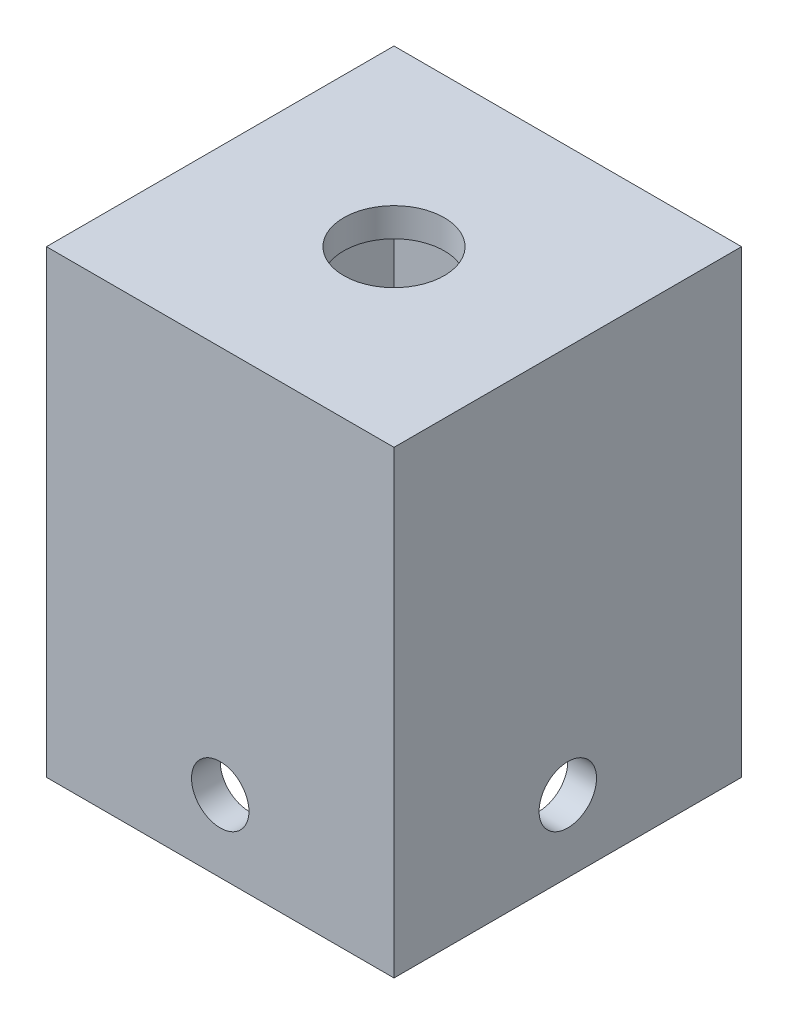
SolidWorks part; units mm, degrees
ref_plane "Front Plane" through (0, 0, 0) normal (0, 0, 1) x (1, 0, 0)
ref_plane "Top Plane" through (0, 0, 0) normal (0, 1, 0) x (1, 0, 0)
ref_plane "Right Plane" through (0, 0, 0) normal (1, 0, 0) x (0, 0, -1)
sketch "Sketch1" plane through (0, 0, 0) normal (0, 1, 0) x (1, 0, 0)
  line L1 (10.1, 10.1) -> (-10.1, 10.1)
  line L2 (10.1, 10.1) -> (10.1, -10.1)
  line L3 (10.1, -10.1) -> (-10.1, -10.1)
  line L4 (-10.1, 10.1) -> (-10.1, -10.1)
  line L5 (10.1, 10.1) -> (-10.1, -10.1) construction
  line L6 (10.1, -10.1) -> (-10.1, 10.1) construction
  line L7 (12.1, 12.1) -> (-12.1, 12.1)
  line L8 (12.1, 12.1) -> (12.1, -12.1)
  line L9 (12.1, -12.1) -> (-12.1, -12.1)
  line L10 (-12.1, 12.1) -> (-12.1, -12.1)
  line L11 (12.1, 12.1) -> (-12.1, -12.1) construction
  line L12 (12.1, -12.1) -> (-12.1, 12.1) construction
  point P0 (0, 0)
  point P6 (0, 0)
  dimension "D1" = 20.2
  dimension "D2" = 20.2
  dimension "D3" = 2
  dimension "D4" = 2
extrude "Boss-Extrude1" add sketch "Sketch1" along normal blind 30
sketch "Sketch2" plane through (0, 0, 12.1) normal (0, 0, 1) x (1, 0, 0)
  circle A0 centre (0, 5) radius 2
  dimension "D1" = 4
  dimension "D2" = 5
extrude "Cut-Extrude1" cut sketch "Sketch2" against normal blind 30
sketch "Sketch3" plane through (12.1, 0, 0) normal (1, 0, 0) x (0, 0, -1)
  circle A0 centre (0, 5) radius 2
  dimension "D1" = 4
  dimension "D2" = 5
extrude "Cut-Extrude2" cut sketch "Sketch3" against normal blind 30
sketch "Sketch4" plane through (0, 30, 0) normal (0, 1, 0) x (1, 0, 0)
  line L1 (12.1, 12.1) -> (-12.1, 12.1)
  line L2 (12.1, 12.1) -> (12.1, -12.1)
  line L3 (12.1, -12.1) -> (-12.1, -12.1)
  line L4 (-12.1, 12.1) -> (-12.1, -12.1)
  line L5 (12.1, 12.1) -> (-12.1, -12.1) construction
  line L6 (12.1, -12.1) -> (-12.1, 12.1) construction
  circle A0 centre (0, 0) radius 3.5
  point P0 (0, 0)
  dimension "D1" = 7
extrude "Boss-Extrude2" add sketch "Sketch4" along normal blind 2
